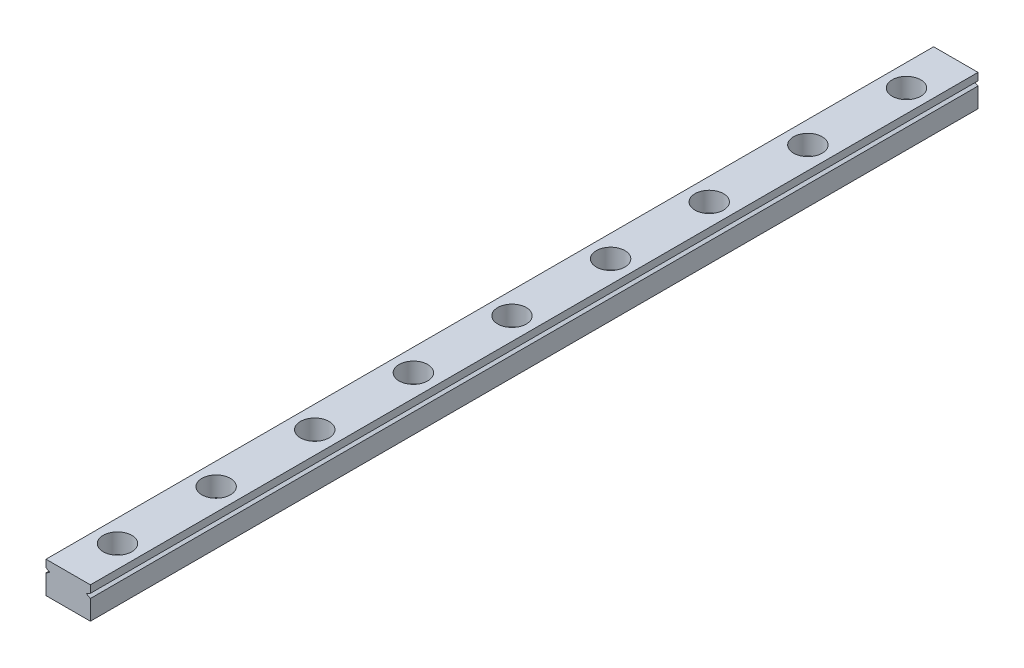
SolidWorks part; units mm, degrees
ref_plane "Front Plane" through (0, 0, 0) normal (0, 0, 1) x (1, 0, 0)
ref_plane "Top Plane" through (0, 0, 0) normal (0, 1, 0) x (1, 0, 0)
ref_plane "Right Plane" through (0, 0, 0) normal (1, 0, 0) x (0, 0, -1)
sketch "Sketch1" plane through (0, 0, 0) normal (0, 0, 1) x (1, 0, 0)
  line L0 (9, 6.4) -> (9, 4.9)
  line L1 (0, 0) -> (9, 0)
  line L2 (0, 0) -> (0, 6.4) construction
  line L3 (0, 6.4) -> (9, 6.4)
  line L4 (9, 0) -> (9, 6.4) construction
  line L5 (9, 4.9) -> (8.2, 4.45)
  line L6 (8.2, 4.45) -> (9, 4)
  line L7 (9, 4) -> (9, 0)
  line L8 (0, 6.4) -> (0, 4.9)
  line L9 (0, 4.9) -> (0.8, 4.45)
  line L10 (0.8, 4.45) -> (0, 4)
  line L11 (0, 4) -> (0, 0)
  line L12 (4.5, 6.4) -> (4.5, 0) construction
  line L13 (9, 4.9) -> (9, 4) construction
  line L14 (9, 4.45) -> (0, 4.45) construction
  dimension "D1" = 9
  dimension "D2" = 6.4
  dimension "D3" = 1.5
  dimension "D4" = 4
  dimension "D5" = 0.8
extrude "Boss-Extrude1" add sketch "Sketch1" along normal blind 180
sketch "Sketch2" plane through (0, 6.4, 0) normal (0, 1, 0) x (1, 0, 0)
  line L0 (4.5, -180) -> (4.5, 0) construction
  line L1 (9, -180) -> (0, -180) construction
  line L2 (9, 0) -> (0, 0) construction
  circle A0 centre (4.5, -170) radius 2.9
  circle A1 centre (4.5, -150) radius 2.9
  circle A2 centre (4.5, -130) radius 2.9
  circle A3 centre (4.5, -110) radius 2.9
  circle A4 centre (4.5, -90) radius 2.9
  circle A5 centre (4.5, -70) radius 2.9
  circle A6 centre (4.5, -50) radius 2.9
  circle A7 centre (4.5, -30) radius 2.9
  circle A8 centre (4.5, -10) radius 2.9
  dimension "D1" = 5.8
  dimension "D2" = 10
  dimension "D3" = 9
extrude "Cut-Extrude1" cut sketch "Sketch2" against normal blind 4
sketch "Sketch3" plane through (0, 2.4, 0) normal (0, 1, 0) x (1, 0, 0)
  circle A0 centre (4.5, -170) radius 1.7
  circle A1 centre (4.5, -170) radius 2.9 construction
  circle A2 centre (4.5, -150) radius 1.7
  circle A3 centre (4.5, -130) radius 1.7
  circle A4 centre (4.5, -110) radius 1.7
  circle A5 centre (4.5, -90) radius 1.7
  circle A6 centre (4.5, -70) radius 1.7
  circle A7 centre (4.5, -50) radius 1.7
  circle A8 centre (4.5, -30) radius 1.7
  circle A9 centre (4.5, -10) radius 1.7
  dimension "D1" = 3.4
  dimension "D2" = 9
extrude "Cut-Extrude2" cut sketch "Sketch3" against normal through all
